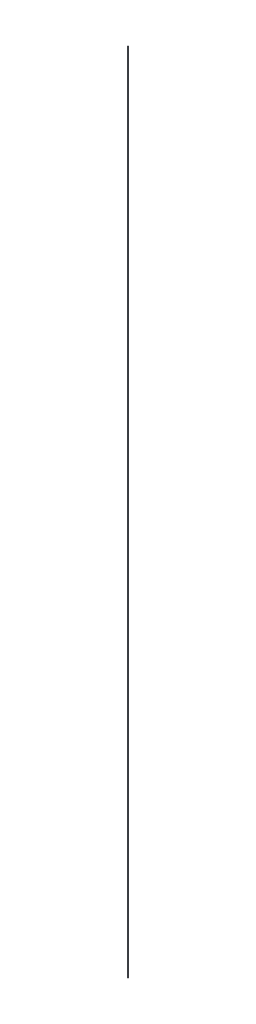
SolidWorks part; units mm, degrees
ref_plane "Front Plane" through (0, 0, 0) normal (0, 0, 1) x (1, 0, 0)
ref_plane "Top Plane" through (0, 0, 0) normal (0, 1, 0) x (1, 0, 0)
ref_plane "Right Plane" through (0, 0, 0) normal (1, 0, 0) x (0, 0, -1)
other "Mesh1"
other "Imported Mesh-1"
other "Imported Mesh-2"
other "Imported Mesh-3"
other "Imported Mesh-4"
other "Imported Mesh-5"
other "Imported Mesh-6"
other "Imported Mesh-7"
other "Imported Mesh-8"
other "Imported Mesh-9"
other "Imported Mesh-10"
other "Imported Mesh-11"
other "Imported Mesh-12"
other "Imported Mesh-13"
other "Imported Mesh-14"
other "Imported Mesh-15"
other "Imported Mesh-16"
other "Imported Mesh-17"
other "Imported Mesh-18"
other "Imported Mesh-19"
other "Imported Mesh-20"
other "Imported Mesh-21"
other "Imported Mesh-22"
other "Imported Mesh-23"
other "Imported Mesh-24"
other "Imported Mesh-25"
other "Imported Mesh-26"
other "Imported Mesh-27"
other "Imported Mesh-28"
other "Imported Mesh-29"
other "Imported Mesh-30"
other "Imported Mesh-31"
sketch "Sketch2" plane through (0, 0, 0) normal (0, 1, 0) x (1, 0, 0)
  line L0 (4526.7445, 0) -> (22584.3109, 0)
  line L1 (22584.3109, 0) -> (22584.3109, -14058.727)
  line L2 (22584.3109, -14058.727) -> (6463.8717, -14058.727)
  line L3 (4526.7445, 0) -> (4526.7445, -12312.4377)
  line L4 (4526.7445, -12312.4377) -> (6463.8717, -14058.727)
  dimension "D1" = 14058.727
  dimension "D2" = 18057.5664
  dimension "D3" = 16120.4392
  dimension "D4" = 12312.4377
sketch "Sketch3" plane through (0, 0, 0) normal (0, 0, 1) x (1, 0, 0)
  line L0 (22456.0745, -24016.2272) -> (22456.0745, 23908.046)
  dimension "D1" = 47924.2732
sketch "Sketch4" plane through (0, 0, 0) normal (0, 1, 0) x (1, 0, 0)
  line L0 (4526.7445, 0) -> (-11059.03, 0)
  line L1 (-11059.03, 0) -> (-11059.03, -12050.9727)
  line L2 (-11059.03, -12050.9727) -> (-6836.1183, -12050.9727)
  line L4 (-6836.1183, -3941.1243) -> (-4840.8494, -3941.1243)
  line L5 (-4840.8494, -3941.1243) -> (-4840.8494, -10651.0149)
  line L6 (-3320.2593, -12050.9727) -> (-1799.6692, -12050.9727)
  line L8 (-1799.6692, -3941.1243) -> (0, -3941.1243)
  line L9 (0, -3941.1243) -> (0, -10409.9358)
  line L10 (1505.273, -12013.0232) -> (4526.7445, -12013.0232)
  line L11 (4526.7445, 0) -> (4526.7445, -12312.4377) construction
  line L12 (4526.7445, -12013.0232) -> (4526.7445, 0)
  line L13 (-6836.1183, -12050.9727) -> (-6836.1183, -3941.1243)
  line L14 (-1799.6692, -12050.9727) -> (-1799.6692, -3941.1243)
  line L15 (0, -10409.9358) -> (1505.273, -12013.0232)
  line L16 (-4840.8494, -10651.0149) -> (-3320.2593, -12050.9727)
  line L18 (-6836.1183, -12050.9727) -> (-5995.2514, -11109.6118)
  point P9 (4526.7445, -6006.5116)
  dimension "D1" = 15585.7745
  dimension "D2" = 12050.9727
  dimension "D3" = 4222.9118
  dimension "D4" = 3041.1801
  dimension "D5" = 4526.7445
  dimension "D6" = 1995.2689
sketch "Sketch5" plane through (0, 0, 0) normal (1, 0, 0) x (0, 0, -1)
  line L0 (-7821.2518, 14742.9531) -> (-7821.2518, -14879.5971)
extrude "Extrude-Thin1" add sketch "Sketch5" along normal blind 10 thin
sketch "Sketch6" plane through (0, 0, 0) normal (0, 0, 1) x (1, 0, 0)
  line L0 (-1763.7577, 13255.9432) -> (10, 13255.9432)
  line L1 (10, 14742.9531) -> (10, -14879.5971) construction
  line L2 (-6909.0547, 12315.8798) -> (-5114.344, 12315.8798)
  line L3 (-11028.7317, 9175.1359) -> (10, 9175.1359)
  line L4 (-11028.7317, 10847.48) -> (-6909.0547, 10847.48)
  line L5 (-11028.7317, 12927.713) -> (-1763.7577, 12927.713)
  line L6 (-6909.0547, 3866.3467) -> (-5919.8463, 3866.3467)
  line L7 (-5785.6884, 3992.3391) -> (-5785.6884, 2985.1114)
  line L8 (-5785.6884, 2985.1114) -> (-5785.6884, 2047.3824)
  dimension "D1" = 9264.9739
  dimension "D2" = 1773.7577
  dimension "D3" = 11038.7317
  dimension "D4" = 4119.677
  dimension "D5" = 989.2084
sketch "Sketch7" plane through (0, 0, 0) normal (0, 0, 1) x (1, 0, 0)
  line L0 (4399.1567, 14834.9382) -> (4399.1567, -15018.411)
